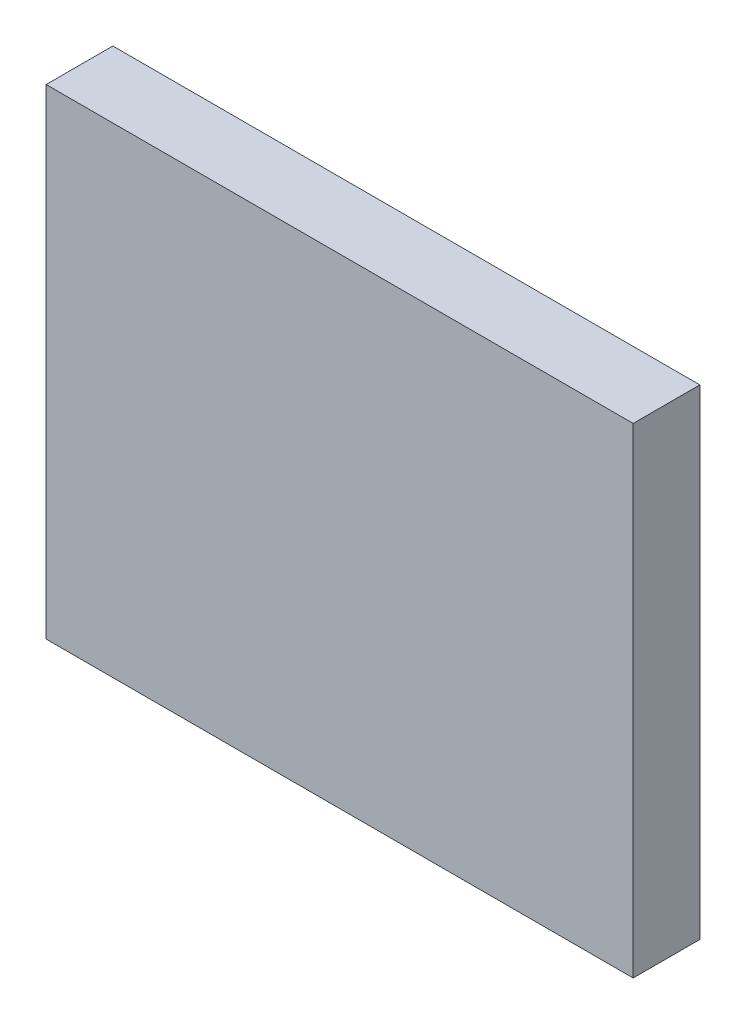
SolidWorks part; units mm, degrees
ref_plane "前视基准面" through (0, 0, 0) normal (0, 0, 1) x (1, 0, 0)
ref_plane "上视基准面" through (0, 0, 0) normal (0, 1, 0) x (1, 0, 0)
ref_plane "右视基准面" through (0, 0, 0) normal (1, 0, 0) x (0, 0, -1)
sketch "草图1" plane through (0, 0, 0) normal (0, 0, 1) x (1, 0, 0)
  line L1 (0, 0) -> (88, 0)
  line L2 (0, 0) -> (0, 72)
  line L3 (0, 72) -> (88, 72)
  line L4 (88, 0) -> (88, 72)
  dimension "D1" = 72
  dimension "D2" = 88
extrude "凸台-拉伸1" add sketch "草图1" along normal blind 10
